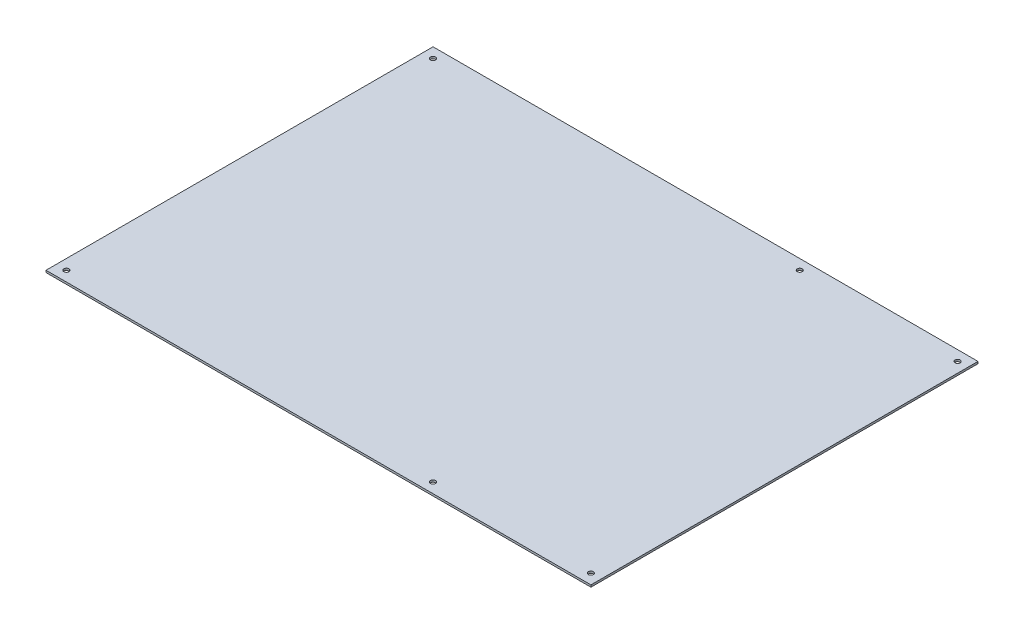
SolidWorks part; units mm, degrees
material "3.1645 (EN AW-2007)"
ref_plane "Přední rovina" through (0, 0, 0) normal (0, 0, 1) x (1, 0, 0)
ref_plane "Horní rovina" through (0, 0, 0) normal (0, 1, 0) x (1, 0, 0)
ref_plane "Pravá rovina" through (0, 0, 0) normal (1, 0, 0) x (0, 0, -1)
sketch "Skica1" plane through (0, 0, 0) normal (0, 1, 0) x (1, 0, 0)
  line L1 (267.5, -190) -> (-267.5, -190)
  line L2 (267.5, -190) -> (267.5, 190)
  line L3 (267.5, 190) -> (-267.5, 190)
  line L4 (-267.5, -190) -> (-267.5, 190)
  line L5 (267.5, -190) -> (-267.5, 190) construction
  line L6 (267.5, 190) -> (-267.5, -190) construction
  circle A0 centre (-257.5293, 180) radius 2.5
  circle A1 centre (-257.5, -180) radius 2.5
  circle A2 centre (102.5, -180) radius 2.5
  circle A3 centre (257.5, -180) radius 2.5
  circle A4 centre (102.5, 180) radius 2.5
  circle A5 centre (257.5, 180) radius 2.5
  point P0 (0, 0)
  dimension "D5" = 5
  dimension "D1" = 535
  dimension "D2" = 380
  dimension "D3" = 9.9707
  dimension "D4" = 10
  dimension "D6" = 10
  dimension "D7" = 10
  dimension "D8" = 10
  dimension "D9" = 10
  dimension "D10" = 10
  dimension "D11" = 155
  dimension "D12" = 155
  dimension "D13" = 10
  dimension "D14" = 10
  dimension "D15" = 10
extrude "Přidat vysunutím1" add sketch "Skica1" along normal blind 2
